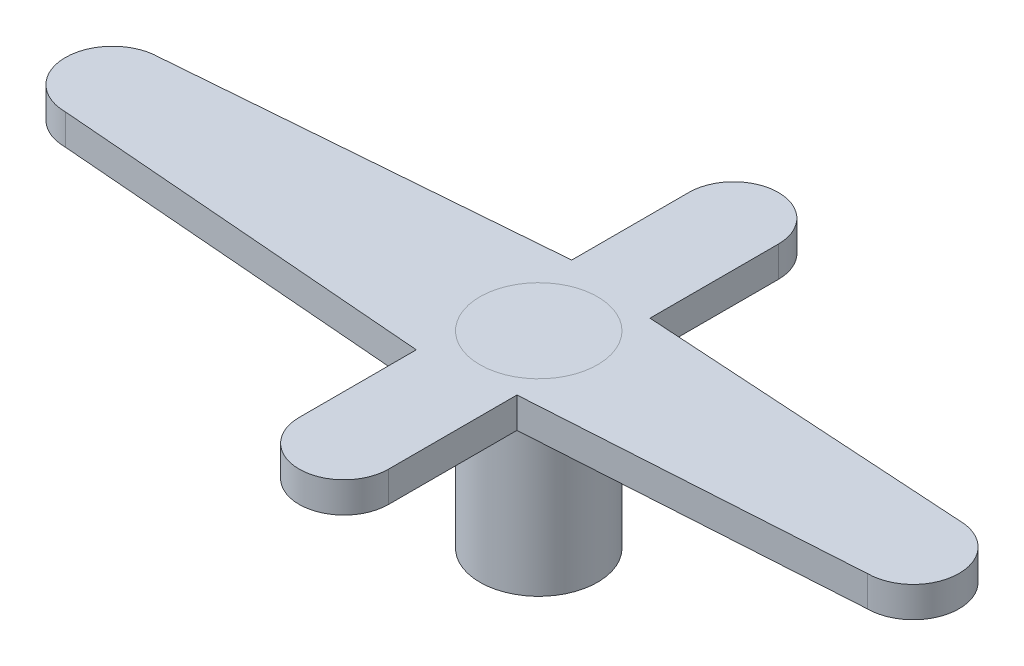
SolidWorks part; units mm, degrees
material "ABS"
ref_plane "Plano frontal" through (0, 0, 0) normal (0, 0, 1) x (1, 0, 0)
ref_plane "Plano superior" through (0, 0, 0) normal (0, 1, 0) x (1, 0, 0)
ref_plane "Plano direito" through (0, 0, 0) normal (1, 0, 0) x (0, 0, -1)
sketch "Sketch1" plane through (0, 0, 0) normal (0, 1, 0) x (1, 0, 0)
  circle A0 centre (0, 0) radius 2.5
  dimension "D1" = 5
extrude "Boss-Extrude1" add sketch "Sketch1" along normal blind 8
sketch "Sketch2" plane through (0, 8, 0) normal (0, 1, 0) x (1, 0, 0)
  line L0 (1.9, 2.825) -> (15.9, 1.95)
  line L1 (-1.9, -8.275) -> (1.9, -8.275)
  line L2 (-1.9, -8.275) -> (-1.9, 8.275)
  line L3 (-1.9, 8.275) -> (1.9, 8.275)
  line L4 (1.9, -8.275) -> (1.9, 8.275)
  line L5 (15.9, -1.95) -> (1.9, -2.825)
  line L6 (-18.1, 2) -> (-1.9, 3.3)
  line L7 (-18.1, -2) -> (-1.9, -3.3)
  circle A0 centre (15.9, 0) radius 1.95
  circle A1 centre (0, 8.275) radius 1.9
  circle A2 centre (0, -8.275) radius 1.9
  circle A3 centre (-18.1, 0) radius 2
  point P12 (1.9, 0)
  circle M7 centre (0, 0) radius 2.5
  dimension "D1" = 3.8
  dimension "D2" = 3.8
  dimension "D4" = 3.9
  dimension "D8" = 4
  dimension "D3" = 16.55
  dimension "D5" = 17.8
  dimension "D6" = 2.825
  dimension "D7" = 2.825
  dimension "D9" = 20
  dimension "D10" = 3.3
  dimension "D11" = 3.3
extrude "Boss-Extrude2" add sketch "Sketch2" against normal blind 1.3 separate body contours A3 | A3 L7 L2 L6 M7 | A1 L2 L4 M7 | L3 A1 | L3 A1 | A2 L4 L2 M7 | L1 A2 | L1 A2 | A0 L0 L4 L5 M7 | A0
equation "\"D7@Sketch2\"=\"D6@Sketch2\""
